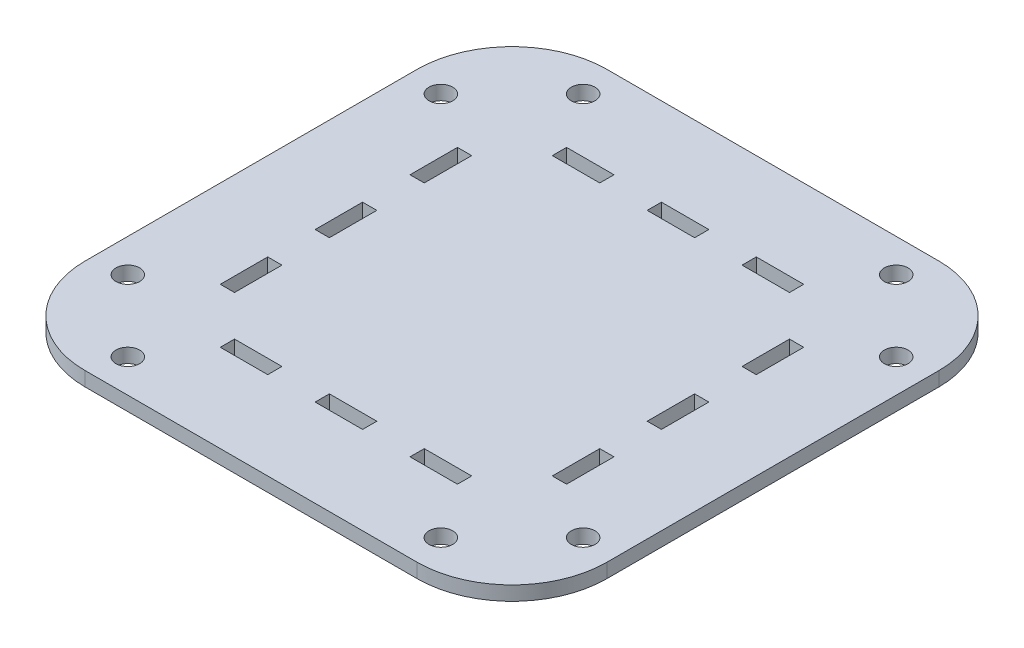
SolidWorks part; units mm, degrees
ref_plane "Front Plane" through (0, 0, 0) normal (0, 0, 1) x (1, 0, 0)
ref_plane "Top Plane" through (0, 0, 0) normal (0, 1, 0) x (1, 0, 0)
ref_plane "Right Plane" through (0, 0, 0) normal (1, 0, 0) x (0, 0, -1)
sketch "Sketch1" plane through (0, 0, 0) normal (0, 1, 0) x (1, 0, 0)
  line L0 (0, 0) -> (0, 48) construction
  line L1 (-55, -55) -> (55, -55)
  line L2 (-55, -55) -> (-55, 55)
  line L3 (-55, 55) -> (55, 55)
  line L4 (55, -55) -> (55, 55)
  line L5 (-55, -55) -> (55, 55) construction
  line L6 (-55, 55) -> (55, -55) construction
  line L7 (-33, 48) -> (33, 48) construction
  circle A0 centre (33, 48) radius 2.5
  circle A1 centre (-33, 48) radius 2.5
  circle A2 centre (48, 33) radius 2.5
  circle A3 centre (48, -33) radius 2.5
  circle A4 centre (33, -48) radius 2.5
  circle A5 centre (-33, -48) radius 2.5
  circle A6 centre (-48, -33) radius 2.5
  circle A7 centre (-48, 33) radius 2.5
  point P1 (0, 0)
  point P12 (0, 48)
  point P29 (0, 0)
  dimension "D5" = 5
  dimension "D6" = 5
  dimension "D1" = 110
  dimension "D2" = 110
  dimension "D3" = 48
  dimension "D4" = 33
  dimension "D7" = 4
extrude "Boss-Extrude1" add sketch "Sketch1" along normal blind 3
fillet "Fillet1" radius 20 4 edges at (55, 1.5, 55) (-55, 1.5, -55) (55, 1.5, -55) (-55, 1.5, 55)
sketch "Sketch2" plane through (0, 3, 0) normal (0, 1, 0) x (1, 0, 0)
  line L0 (0, 0) -> (0, 35) construction
  line L1 (5, 33.5) -> (15, 33.5) construction
  line L2 (-5, 33.5) -> (5, 33.5)
  line L3 (-5, 33.5) -> (-5, 36.5)
  line L4 (-5, 36.5) -> (5, 36.5)
  line L5 (5, 33.5) -> (5, 36.5)
  line L6 (-5, 33.5) -> (5, 36.5) construction
  line L7 (-5, 36.5) -> (5, 33.5) construction
  line L8 (-5, 33.5) -> (-15, 33.5)
  line L9 (15, 33.5) -> (25, 33.5)
  line L10 (15, 33.5) -> (15, 36.5)
  line L11 (15, 36.5) -> (25, 36.5)
  line L12 (25, 33.5) -> (25, 36.5)
  line L13 (15, 33.5) -> (25, 36.5) construction
  line L14 (15, 36.5) -> (25, 33.5) construction
  line L15 (33.5, 15) -> (33.5, 25)
  line L16 (-15, 33.5) -> (-25, 33.5)
  line L17 (-15, 33.5) -> (-15, 36.5)
  line L18 (-15, 36.5) -> (-25, 36.5)
  line L19 (-25, 33.5) -> (-25, 36.5)
  line L20 (-15, 33.5) -> (-25, 36.5) construction
  line L21 (-15, 36.5) -> (-25, 33.5) construction
  line L22 (33.5, 15) -> (36.5, 15)
  line L23 (36.5, 15) -> (36.5, 25)
  line L24 (33.5, 25) -> (36.5, 25)
  line L25 (33.5, 5) -> (36.5, 5)
  line L26 (36.5, 5) -> (36.5, -5)
  line L27 (33.5, -5) -> (36.5, -5)
  line L28 (33.5, 5) -> (33.5, -5)
  line L29 (33.5, -15) -> (36.5, -15)
  line L30 (36.5, -15) -> (36.5, -25)
  line L31 (33.5, -15) -> (33.5, -25)
  line L32 (33.5, -25) -> (36.5, -25)
  line L33 (15, -33.5) -> (25, -33.5)
  line L34 (15, -33.5) -> (15, -36.5)
  line L35 (15, -36.5) -> (25, -36.5)
  line L36 (25, -33.5) -> (25, -36.5)
  line L37 (5, -33.5) -> (5, -36.5)
  line L38 (5, -36.5) -> (-5, -36.5)
  line L39 (-5, -33.5) -> (-5, -36.5)
  line L40 (5, -33.5) -> (-5, -33.5)
  line L41 (-15, -33.5) -> (-15, -36.5)
  line L42 (-15, -36.5) -> (-25, -36.5)
  line L43 (-15, -33.5) -> (-25, -33.5)
  line L44 (-25, -33.5) -> (-25, -36.5)
  line L45 (-33.5, -15) -> (-33.5, -25)
  line L46 (-33.5, -15) -> (-36.5, -15)
  line L47 (-36.5, -15) -> (-36.5, -25)
  line L48 (-33.5, -25) -> (-36.5, -25)
  line L49 (-33.5, -5) -> (-36.5, -5)
  line L50 (-36.5, -5) -> (-36.5, 5)
  line L51 (-33.5, 5) -> (-36.5, 5)
  line L52 (-33.5, -5) -> (-33.5, 5)
  line L53 (-33.5, 15) -> (-36.5, 15)
  line L54 (-36.5, 15) -> (-36.5, 25)
  line L55 (-33.5, 15) -> (-33.5, 25)
  line L56 (-33.5, 25) -> (-36.5, 25)
  point P11 (20, 35)
  point P16 (-20, 35)
  point P56 (0, 0)
  dimension "D1" = 35
  dimension "D2" = 3
  dimension "D3" = 10
  dimension "D4" = 10
  dimension "D5" = 10
  dimension "D6" = 3
  dimension "D7" = 10
  dimension "D8" = 3
  dimension "D9" = 10
  dimension "D10" = 4
extrude "Cut-Extrude1" cut sketch "Sketch2" against normal through all contours L48 L45 L46 L47 | L49 L52 L51 L50 | L19 L16 L17 L18 | L2 L5 L4 L3 | L9 L12 L11 L10 | L24 L15 L22 L23 | L25 L28 L27 L26 | L31 L32 L30 L29 | L36 L33 L34 L35 | L37 L40 L39 L38 | L43 L44 L42 L41 | L54 L56 L55 L53
